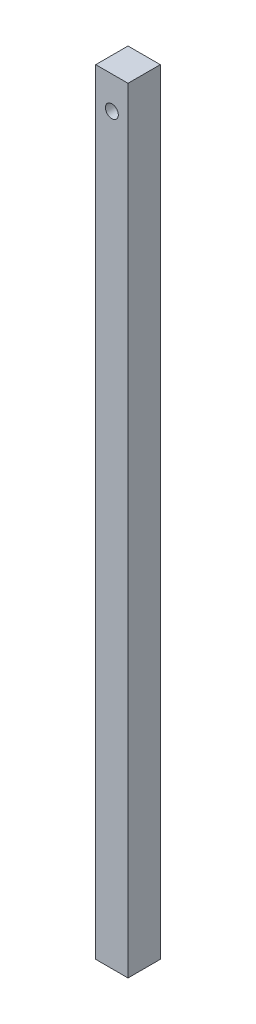
SolidWorks part; units mm, degrees
material "Brass"
ref_plane "Front Plane" through (0, 0, 0) normal (0, 0, 1) x (1, 0, 0)
ref_plane "Top Plane" through (0, 0, 0) normal (0, 1, 0) x (1, 0, 0)
ref_plane "Right Plane" through (0, 0, 0) normal (1, 0, 0) x (0, 0, -1)
sketch "Sketch1" plane through (0, 0, 0) normal (0, 0, 1) x (1, 0, 0)
  line L0 (-2.5, 0) -> (2.5, 0)
  line L1 (2.5, 0) -> (2.5, 120)
  line L2 (2.5, 120) -> (-2.5, 120)
  line L3 (-2.5, 120) -> (-2.5, 0)
  dimension "D1" = 5
  dimension "D2" = 120
  dimension "D3" = 2.5
extrude "Boss-Extrude1" add sketch "Sketch1" along normal blind 5
sketch "Sketch2" plane through (0, 0, 0) normal (0, 0, 1) x (1, 0, 0)
  circle A0 centre (0, 115) radius 1
  dimension "D2" = 2
  dimension "D1" = 115
extrude "Cut-Extrude1" cut sketch "Sketch2" against normal mid plane 20
